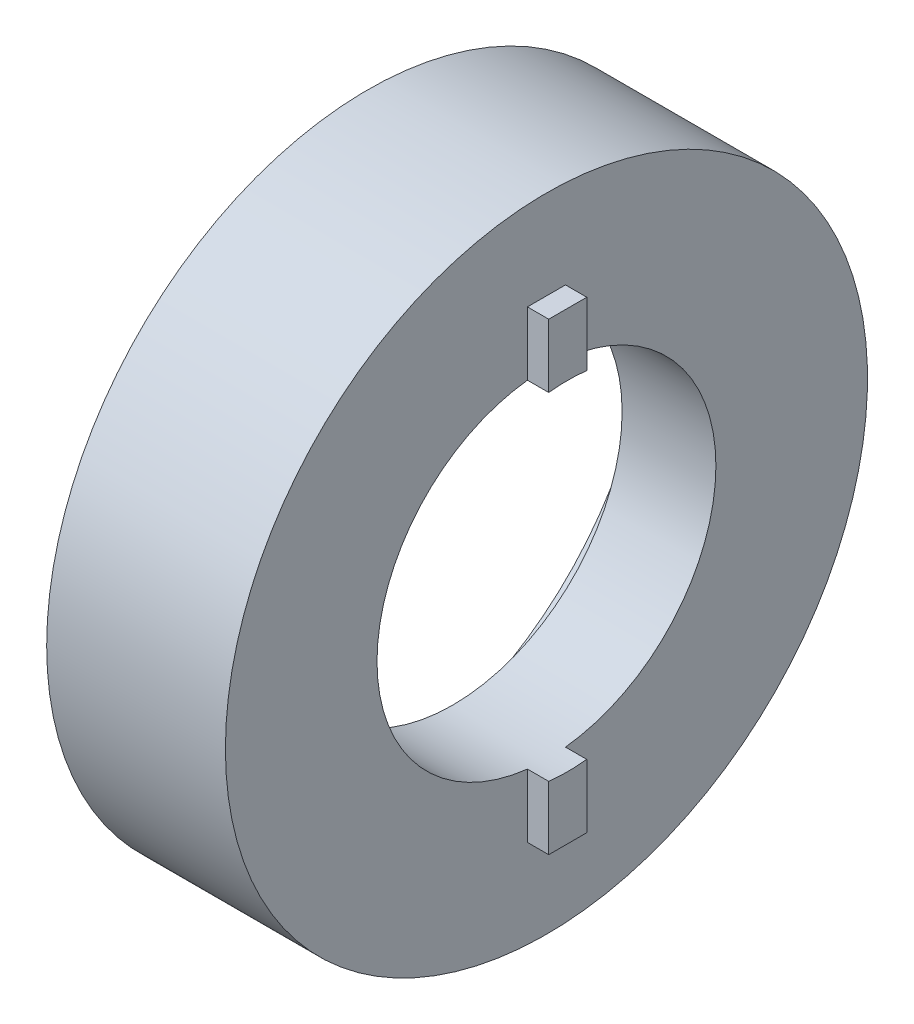
SolidWorks part; units mm, degrees
material "7075-T6 (SN)"
ref_plane "Front Plane" through (0, 0, 0) normal (0, 0, 1) x (1, 0, 0)
ref_plane "Top Plane" through (0, 0, 0) normal (0, 1, 0) x (1, 0, 0)
ref_plane "Right Plane" through (0, 0, 0) normal (1, 0, 0) x (0, 0, -1)
sketch "Sketch13" plane through (0, 0, 0) normal (1, 0, 0) x (0, 0, -1)
  circle A0 centre (0, 0) radius 36
  dimension "D1" = 72
extrude "Boss-Extrude11" add sketch "Sketch13" along normal blind 20.0406 separate body
sketch "Sketch14" plane through (0, 0, 0) normal (-1, 0, 0) x (0, 0, 1)
  circle A0 centre (0, 0) radius 31.75
  circle A1 centre (0, 0) radius 36 construction
  dimension "D1" = 63.5
extrude "Cut-Extrude2" cut sketch "Sketch14" against normal blind 9.525
sketch "Sketch16" plane through (20.0406, 0, 0) normal (1, 0, 0) x (0, 0, -1)
  line L1 (2.1336, 26) -> (-2.1336, 26)
  line L2 (2.1336, 26) -> (2.1336, -26)
  line L3 (2.1336, -26) -> (-2.1336, -26)
  line L4 (-2.1336, 26) -> (-2.1336, -26)
  line L5 (2.1336, 26) -> (-2.1336, -26) construction
  line L6 (2.1336, -26) -> (-2.1336, 26) construction
  point P0 (0, 0)
  dimension "D1" = 4.2672
  dimension "D2" = 52
extrude "Boss-Extrude12" add sketch "Sketch16" along normal blind 2.3876
sketch "Sketch15" plane through (0, 0, 0) normal (-1, 0, 0) x (0, 0, 1)
  circle A0 centre (0, 0) radius 19
  circle A1 centre (0, 0) radius 36 construction
  dimension "D1" = 38
extrude "Cut-Extrude3" cut sketch "Sketch15" against normal through all
